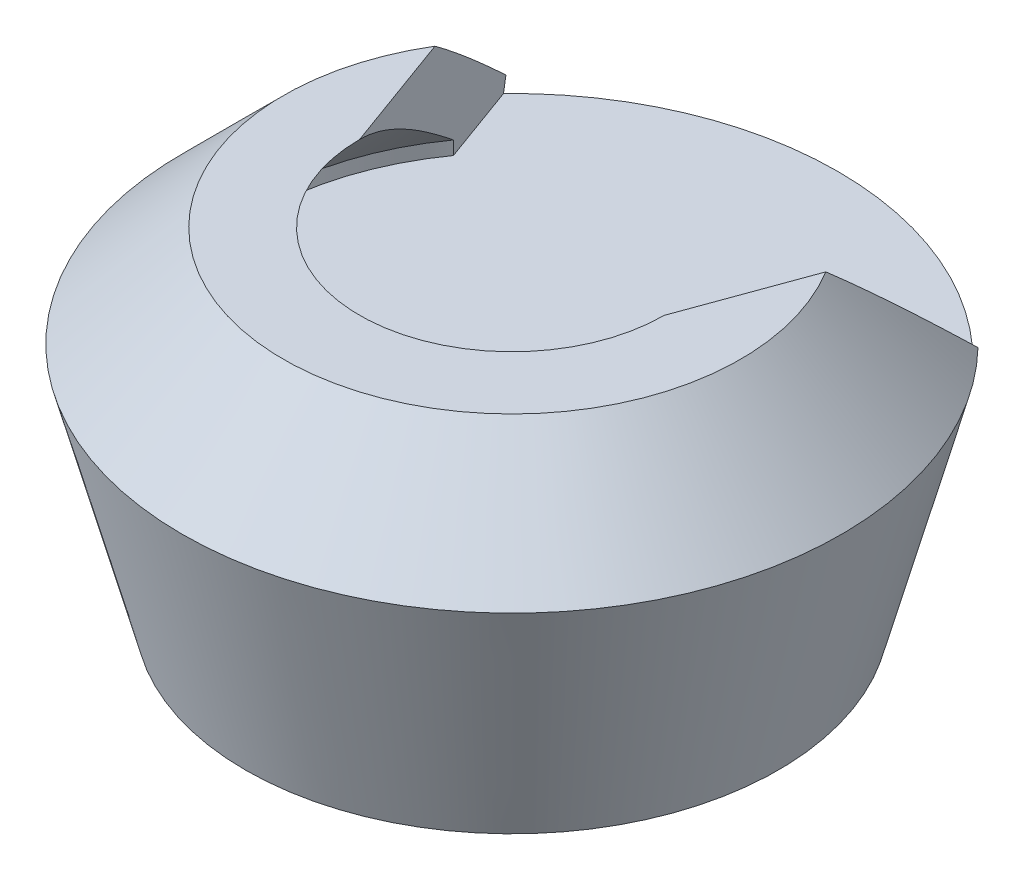
SolidWorks part; units mm, degrees
ref_plane "Front Plane" through (0, 0, 0) normal (0, 0, 1) x (1, 0, 0)
ref_plane "Top Plane" through (0, 0, 0) normal (0, 1, 0) x (1, 0, 0)
ref_plane "Right Plane" through (0, 0, 0) normal (1, 0, 0) x (0, 0, -1)
sketch "Sketch7" plane through (0, 0, 0) normal (0, 0, 1) x (1, 0, 0)
  line L0 (0, 0) -> (0, 9.2837) construction
  line L1 (0, 0) -> (9.2837, 0) construction
  line L2 (9.2837, 0) -> (9.5531, 0) construction
  line L3 (0, 9.2837) -> (9.2837, 0) construction
  line L4 (9.5531, 0) -> (5.7431, 3.81)
  line L5 (5.7431, 3.81) -> (8.6168, 3.81)
  line L6 (8.6168, 3.81) -> (12.4268, 0)
  line L7 (12.4268, 0) -> (9.5531, 0)
  dimension "D1" = 9.2837
  dimension "D2" = 45
  dimension "D3" = 2.032
  dimension "D4" = 0.381
  dimension "D5" = 3.81
revolve "Revolve1" add sketch "Sketch7" angle 360 about L0
sketch "Sketch8" plane through (0, 0, 0) normal (0, -1, 0) x (1, 0, 0)
  circle A1 centre (0, 0) radius 12.4268 construction
  circle A2 centre (0, 0) radius 12.4268
extrude "Boss-Extrude3" add sketch "Sketch8" along normal blind 8.89 draft 15
sketch "Sketch9" plane through (0, 0, 0) normal (0, 1, 0) x (1, 0, 0)
  circle A0 centre (0, 0) radius 9.5531 construction
  circle A1 centre (0, 0) radius 9.5531
extrude "Cut-Extrude1" cut sketch "Sketch9" against normal blind 0.508
sketch "Sketch13" plane through (0, 3.81, 0) normal (0, 1, 0) x (1, 0, 0)
  line L0 (-5.7431, 0) -> (-8.8998, 8.6729)
  line L1 (-5.7431, 0) -> (0, 0) construction
  line L2 (-5.7431, 0) -> (-5.7431, 11.0201) construction
  line L3 (5.7431, 0) -> (8.8998, 8.6729)
  line L4 (5.7431, 0) -> (5.7431, 11.0201) construction
  circle A0 centre (0, 0) radius 5.7431 construction
  circle A1 centre (0, 0) radius 12.4268 construction
  arc A2 (5.7431, 0) -> (-5.7431, 0) centre (0, 0) ccw
  arc A3 (8.8998, 8.6729) -> (-8.8998, 8.6729) centre (0, 0) ccw
  dimension "D1" = 20
  dimension "D2" = 20
extrude "Cut-Extrude4" cut sketch "Sketch13" against normal up to surface (4.318 mm away) up to face at (0, -0.508, 9.5531)
